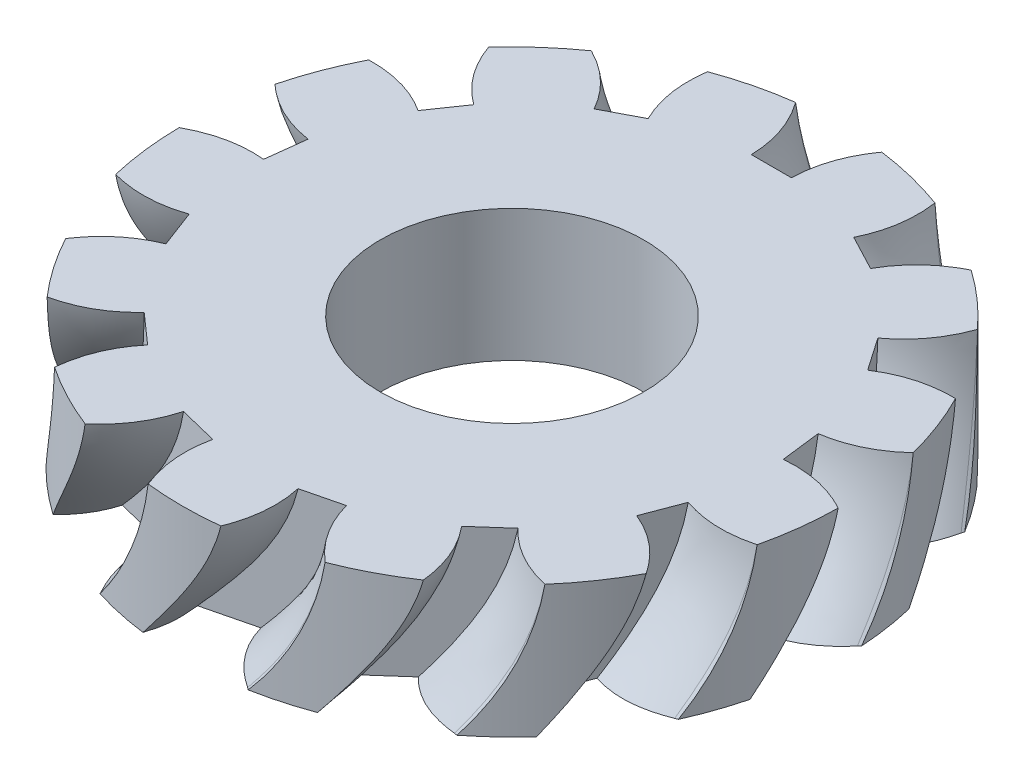
SolidWorks part; units mm, degrees
ref_plane "前视基准面" through (0, 0, 0) normal (0, 0, 1) x (1, 0, 0)
ref_plane "上视基准面" through (0, 0, 0) normal (0, 1, 0) x (1, 0, 0)
ref_plane "右视基准面" through (0, 0, 0) normal (1, 0, 0) x (0, 0, -1)
other "Configuration Table"
sketch "草图1" plane through (0, 0, 0) normal (0, 1, 0) x (1, 0, 0)
  circle A0 centre (0, 0) radius 75
  circle A1 centre (0, 0) radius 30
  dimension "D1" = 150
extrude "凸台-拉伸1" add sketch "草图1" along normal blind 30
sketch "草图2" plane through (0, 30, 0) normal (0, 1, 0) x (1, 0, 0)
  line L0 (0, 75) -> (0, 0) construction
  line L1 (-4.5486, 59.0279) -> (4.5486, 59.0279)
  circle A0 centre (0, 0) radius 75 construction
  arc A3 (14.9424, 78.5406) -> (-14.9424, 78.5406) centre (0, 0) ccw
  spline S0 degree 2 poles (9.803, 74.3566) (4.7842, 67.406) (4.5486, 59.0279) knots 0 0 0 1 1 1
  spline S1 degree 2 poles (-9.803, 74.3566) (-4.7842, 67.406) (-4.5486, 59.0279) knots 0 0 0 1 1 1
  spline S2 degree 2 poles (9.803, 74.3566) (11.6362, 77.3511) (14.9424, 78.5406) knots 0 0 0 1 1 1
  spline S3 degree 2 poles (-9.803, 74.3566) (-11.6362, 77.3511) (-14.9424, 78.5406) knots 0 0 0 1 1 1
ref_plane "基准面1" through (0, 0, -75) normal (0, 0, 1) x (1, 0, 0)
sketch "草图4" plane through (0, 0, -75) normal (0, 0, 1) x (1, 0, 0)
  line L1 (14.9424, 30) -> (-14.9424, 30) construction
  spline S0 degree 3 poles (0, 30) (2.6349, 15.7364) (13.0196, 4.7616) (22.4947, -5.3483) knots 0 0 0 0 1 1 1 1
sweep "切除-扫描2" cut profiles "草图2" path "草图4"
sketch "草图5" plane through (0, 0, 0) normal (1, 0, 0) x (0, 0, -1)
  line L0 (0, 57.7756) -> (0, -20.3771) construction
pattern_circular "阵列(圆周)1" count 13 over 360 about axis through (0, 57.7756, 0) along (0, -1, 0) of "切除-扫描2"
